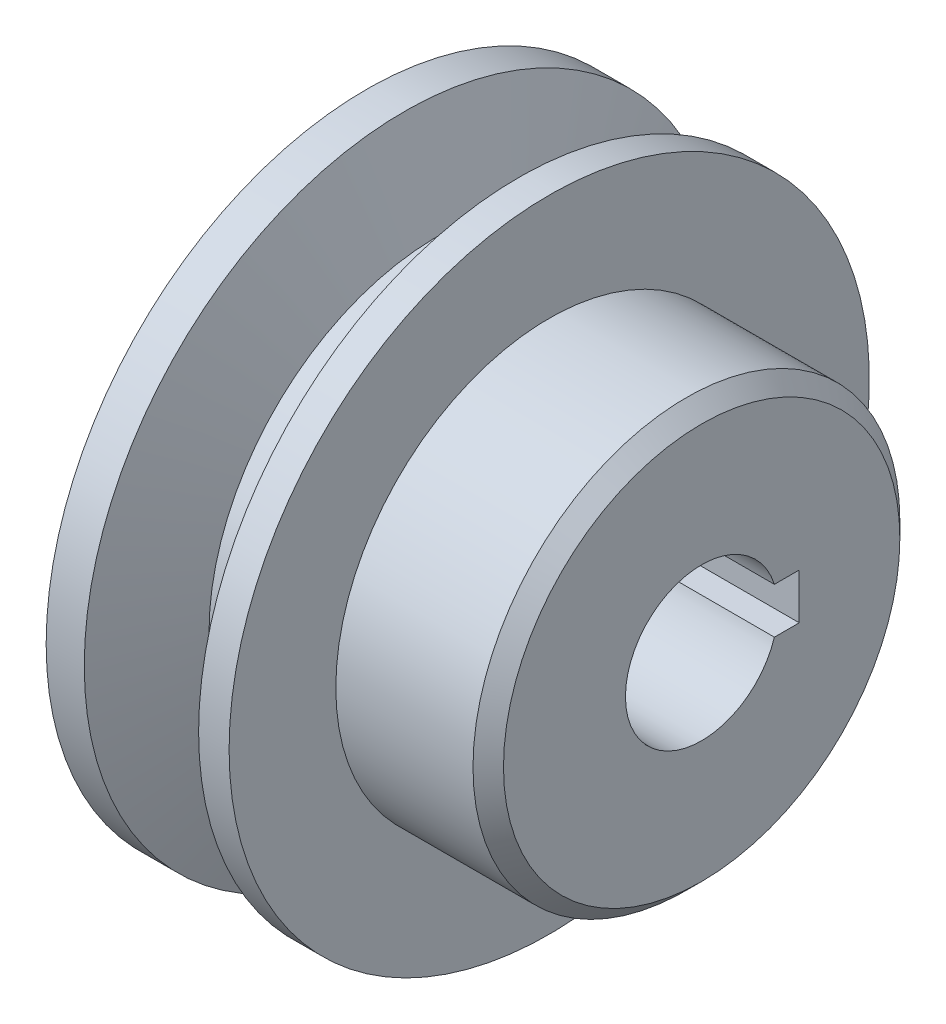
SolidWorks part; units mm, degrees
material "AISI 1035 Steel (SS)"
ref_plane "Front Plane" through (0, 0, 0) normal (0, 0, 1) x (1, 0, 0)
ref_plane "Top Plane" through (0, 0, 0) normal (0, 1, 0) x (1, 0, 0)
ref_plane "Right Plane" through (0, 0, 0) normal (1, 0, 0) x (0, 0, -1)
sketch "Sketch1" plane through (0, 0, 0) normal (0, 0, 1) x (1, 0, 0)
  line L0 (-92.4779, 0) -> (107.3626, 0) construction
  line L1 (-12, 5) -> (10, 5)
  line L2 (10, 5) -> (10, 14)
  line L3 (10, 14) -> (0, 14)
  line L4 (0, 14) -> (0, 21)
  line L5 (0, 21) -> (-2, 21)
  line L9 (-9.5, 21) -> (-12, 21)
  line L10 (-12, 21) -> (-12, 5)
  line L11 (-9.5, 21) -> (-7.3162, 15)
  line L12 (-7.3162, 15) -> (-4.1838, 15)
  line L13 (-4.1838, 15) -> (-2, 21)
  line L14 (-5.75, 15) -> (-5.75, 39.5612) construction
  dimension "D1" = 2
  dimension "D2" = 12
  dimension "D3" = 21
  dimension "D4" = 14
  dimension "D5" = 5
  dimension "D6" = 15
  dimension "D7" = 20
  dimension "D8" = 2.5
  dimension "D9" = 20
  dimension "D10" = 22
revolve "Revolve1" add sketch "Sketch1" angle 360 about L0
chamfer "Chamfer1" distance 1 angle 45 1 edges at (10, 0, 14)
sketch "Sketch2" plane through (10, 0, 0) normal (1, 0, 0) x (0, 0, -1)
  line L1 (4.7697, 1.5) -> (6.4, 1.5)
  line L3 (4.7697, -1.5) -> (6.4, -1.5)
  line L4 (6.4, 1.5) -> (6.4, -1.5)
  circle A0 centre (0, 0) radius 5 construction
  arc A1 (4.7697, -1.5) -> (4.7697, 1.5) centre (0, 0) ccw
  point P0 (5, 0)
  dimension "D1" = 10
  dimension "D2" = 3
  dimension "D3" = 6.4
  dimension "D4" = 1.6303
extrude "Cut-Extrude1" cut sketch "Sketch2" against normal up to next
